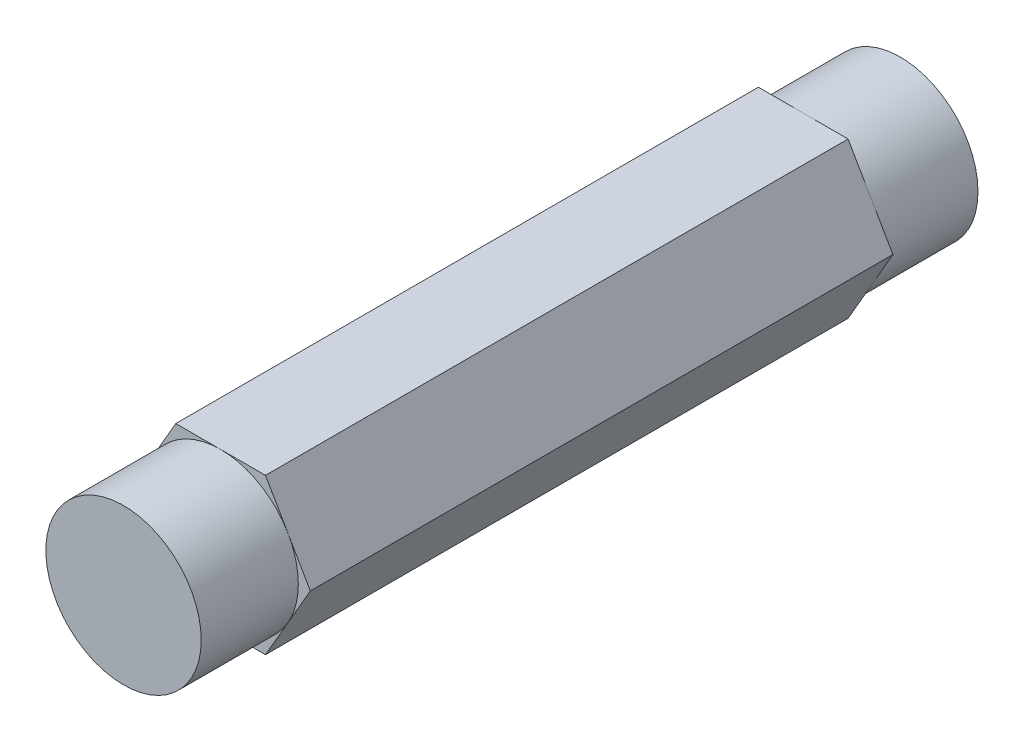
SolidWorks part; units mm, degrees
material "7075-T6 (SN)"
ref_plane "Front Plane" through (0, 0, 0) normal (0, 0, 1) x (1, 0, 0)
ref_plane "Top Plane" through (0, 0, 0) normal (0, 1, 0) x (1, 0, 0)
ref_plane "Right Plane" through (0, 0, 0) normal (1, 0, 0) x (0, 0, -1)
sketch "Sketch1" plane through (0, 0, 0) normal (0, 0, 1) x (1, 0, 0)
  line L1 (7.3323, 0) -> (3.6662, 6.35)
  line L2 (3.6662, 6.35) -> (-3.6662, 6.35)
  line L3 (-3.6662, 6.35) -> (-7.3323, 0)
  line L4 (-7.3323, 0) -> (-3.6662, -6.35)
  line L5 (-3.6662, -6.35) -> (3.6662, -6.35)
  line L6 (3.6662, -6.35) -> (7.3323, 0)
  circle A0 centre (0, 0) radius 6.35 construction
  dimension "D1" = 12.7
extrude "Boss-Extrude1" add sketch "Sketch1" along normal mid plane 63.5
sketch "Sketch2" plane through (0, 0, 31.75) normal (0, 0, 1) x (1, 0, 0)
  circle A0 centre (0, 0) radius 6.35
  dimension "D1" = 12.7
extrude "Cut-Extrude-Thin1" cut sketch "Sketch2" against normal blind 7.9375 thin
mirror "Mirror1" about plane through (0, 0, 0) normal (0, 0, 1) of "Cut-Extrude-Thin1"
